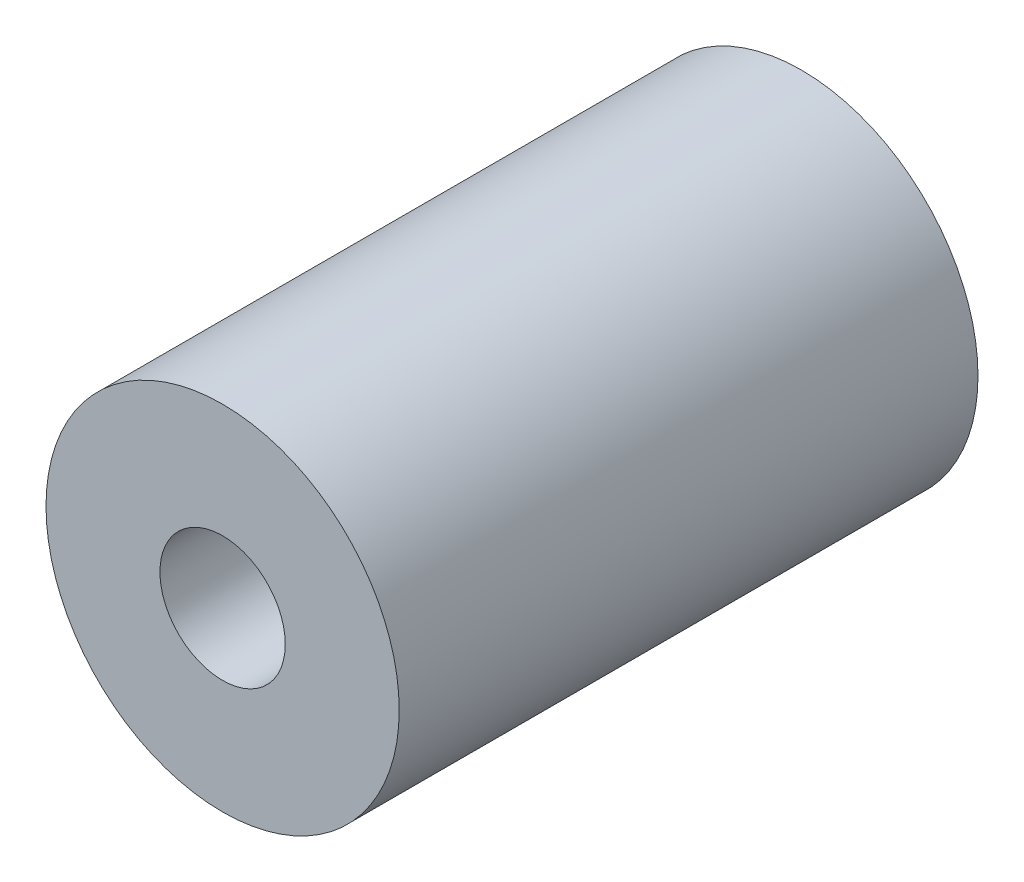
SolidWorks part; units mm, degrees
ref_plane "Front Plane" through (0, 0, 0) normal (0, 0, 1) x (1, 0, 0)
ref_plane "Top Plane" through (0, 0, 0) normal (0, 1, 0) x (1, 0, 0)
ref_plane "Right Plane" through (0, 0, 0) normal (1, 0, 0) x (0, 0, -1)
sketch "Sketch1" plane through (0, 0, 0) normal (0, 0, 1) x (1, 0, 0)
  circle A0 centre (0, 0) radius 2.75
  circle A1 centre (0, 0) radius 7.75
  dimension "D1" = 5.5
  dimension "D3" = 15.5
  dimension "D2" = 5
extrude "Boss-Extrude1" add sketch "Sketch1" along normal mid plane 25.4
